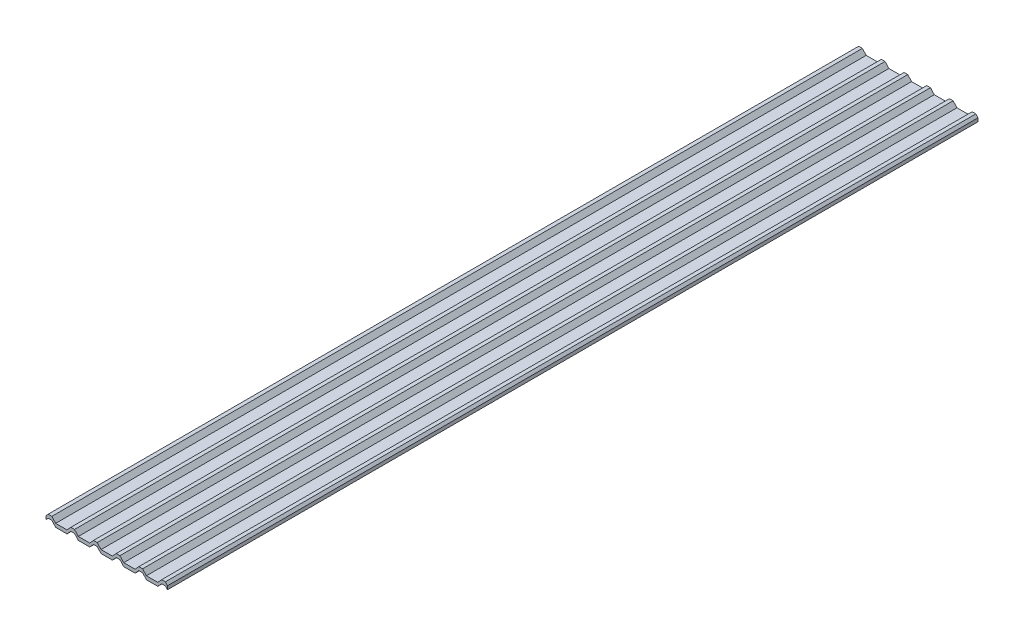
SolidWorks part; units mm, degrees
material "Epoxy, Unfilled"
ref_plane "Plano frontal" through (0, 0, 0) normal (0, 0, 1) x (1, 0, 0)
ref_plane "Plano superior" through (0, 0, 0) normal (0, 1, 0) x (1, 0, 0)
ref_plane "Plano direito" through (0, 0, 0) normal (1, 0, 0) x (0, 0, -1)
sketch "Esboço1" plane through (0, 0, 0) normal (0, 0, 1) x (1, 0, 0)
  line L0 (0, 0) -> (32, 0)
  line L1 (65, -36) -> (163, -36)
  line L3 (0, 0) -> (-33, -36)
  line L4 (32, 0) -> (65, -36)
  line L5 (196, 0) -> (228, 0)
  line L6 (261, -36) -> (359, -36)
  line L7 (196, 0) -> (163, -36)
  line L8 (228, 0) -> (261, -36)
  line L9 (-33, -36) -> (-131, -36)
  line L10 (392, 0) -> (424, 0)
  line L11 (457, -36) -> (555, -36)
  line L12 (392, 0) -> (359, -36)
  line L13 (424, 0) -> (457, -36)
  line L14 (588, 0) -> (620, 0)
  line L15 (653, -36) -> (751, -36)
  line L16 (588, 0) -> (555, -36)
  line L17 (620, 0) -> (653, -36)
  line L18 (-196, 0) -> (-164, 0)
  line L19 (-196, 0) -> (-214.2729, -20)
  line L20 (-164, 0) -> (-131, -36)
  line L23 (784, 0) -> (816, 0)
  line L24 (784, 0) -> (751, -36)
  line L25 (816, 0) -> (834.5668, -20)
  line L26 (784, 30) -> (751, -6)
  line L27 (228, 30) -> (261, -6)
  line L28 (653, -6) -> (751, -6)
  line L29 (0, 30) -> (-33, -6)
  line L30 (424, 30) -> (457, -6)
  line L31 (588, 30) -> (555, -6)
  line L32 (-196, 30) -> (-214.2729, 10)
  line L33 (261, -6) -> (359, -6)
  line L34 (784, 30) -> (816, 30)
  line L35 (0, 30) -> (32, 30)
  line L36 (65, -6) -> (163, -6)
  line L37 (392, 30) -> (359, -6)
  line L38 (588, 30) -> (620, 30)
  line L39 (816, 30) -> (834.5668, 10)
  line L40 (-33, -6) -> (-131, -6)
  line L41 (-196, 30) -> (-164, 30)
  line L42 (-164, 30) -> (-131, -6)
  line L43 (196, 30) -> (228, 30)
  line L44 (32, 30) -> (65, -6)
  line L45 (196, 30) -> (163, -6)
  line L46 (620, 30) -> (653, -6)
  line L47 (392, 30) -> (424, 30)
  line L48 (457, -6) -> (555, -6)
  line L49 (-214.2729, 10) -> (-214.2729, -20)
  line L50 (834.5668, 10) -> (834.5668, -20)
  point P8 (16, -36)
  point P12 (212, -36)
  point P18 (408, -36)
  point P23 (604, -36)
  point P36 (16, -6)
  point P40 (212, -6)
  point P46 (408, -6)
  point P51 (604, -6)
  dimension "D1" = 98
  dimension "D2" = 98
sketch "Esboço2" plane through (0, 0, 0) normal (0, 0, 1) x (1, 0, 0)
  line L0 (0, 30) -> (32, 30)
  line L1 (65, -6) -> (163, -6)
  line L3 (0, 30) -> (-33, -6)
  line L4 (32, 30) -> (65, -6)
  line L5 (196, 30) -> (228, 30)
  line L6 (261, -6) -> (359, -6)
  line L7 (196, 30) -> (163, -6)
  line L8 (228, 30) -> (261, -6)
  line L9 (-33, -6) -> (-131, -6)
  line L10 (392, 30) -> (424, 30)
  line L11 (457, -6) -> (555, -6)
  line L12 (392, 30) -> (359, -6)
  line L13 (424, 30) -> (457, -6)
  line L14 (588, 30) -> (620, 30)
  line L15 (653, -6) -> (751, -6)
  line L16 (588, 30) -> (555, -6)
  line L17 (620, 30) -> (653, -6)
  line L18 (-196, 30) -> (-164, 30)
  line L19 (-196, 30) -> (-214.2729, 10)
  line L20 (-164, 30) -> (-131, -6)
  line L23 (784, 30) -> (816, 30)
  line L24 (784, 30) -> (751, -6)
  line L25 (816, 30) -> (834.5668, 10)
  point P8 (16, -6)
  point P12 (212, -6)
  point P18 (408, -6)
  point P23 (604, -6)
  dimension "D1" = 98
  dimension "D2" = 98
extrude "Ressalto-extrusão1" add sketch "Esboço1" along normal blind 7000 contours L40 L42 L41 L32 L49 L19 L18 L20 L9 L3 L0 L4 L1 L7 L5 L8 L6 L12 L10 L13 L11 L16 L14 L17 L15 L24 L23 L25 L50 L39 L34 L26 L28 L46 L38 L31 L48 L30 L47 L37 L33 L27 L43 L45 L36 L44 L35 L29
